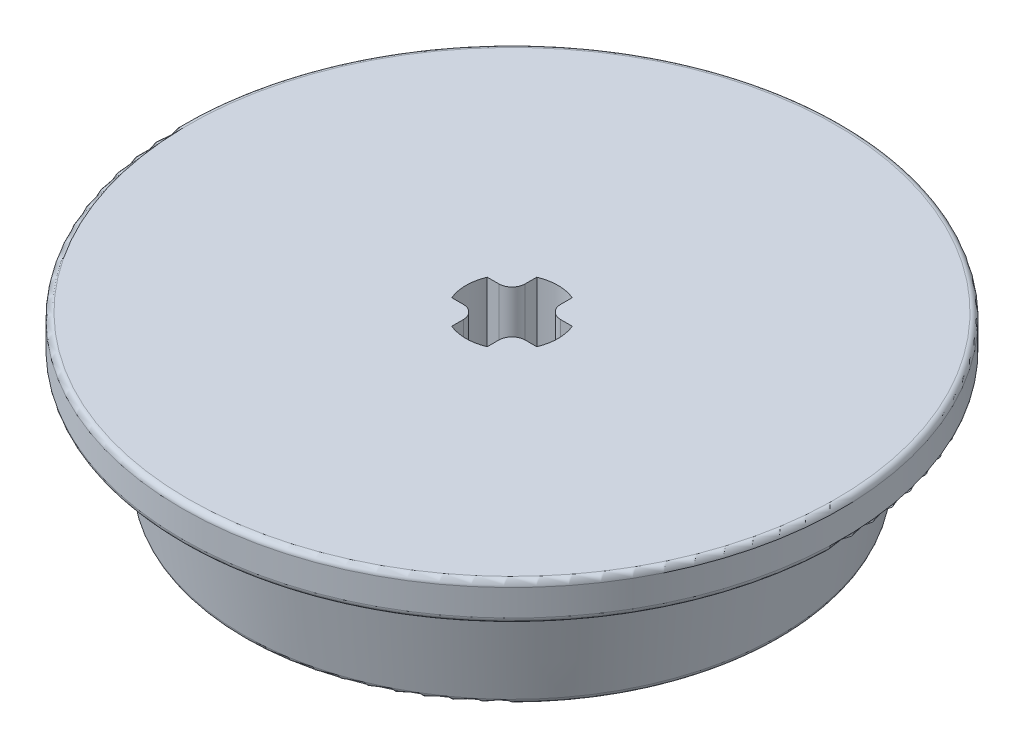
SolidWorks part; units mm, degrees
ref_plane "Front Plane" through (0, 0, 0) normal (0, 0, 1) x (1, 0, 0)
ref_plane "Top Plane" through (0, 0, 0) normal (0, 1, 0) x (1, 0, 0)
ref_plane "Right Plane" through (0, 0, 0) normal (1, 0, 0) x (0, 0, -1)
sketch "Sketch1" plane through (0, 0, 0) normal (0, 1, 0) x (1, 0, 0)
  line L2 (0, 0) -> (0, 47.5777) construction
  line L3 (0, 0) -> (50000, 0) construction
  line L6 (-0.89, 0.89) -> (0, 0) construction
  line L7 (0, 0) -> (0.89, 0.89) construction
  line L12 (2.39, 0) -> (2.39, 3.5727) construction
  line L13 (0, 2.39) -> (50000, 2.39) construction
  line L14 (-2.39, 0.4111) -> (-2.39, -49999.5889) construction
  line L15 (0.2318, -2.39) -> (-49999.7682, -2.39) construction
  line L16 (0, 0) -> (-0.89, -0.89) construction
  line L17 (0, 0) -> (0.89, -0.89) construction
  line L18 (-0.94, 0.94) -> (-2.2517, 0.94)
  line L19 (-2.2517, -0.94) -> (-0.94, -0.94)
  line L20 (-0.94, -0.94) -> (-0.94, -2.2517)
  line L21 (0.94, -2.2517) -> (0.94, -0.94)
  line L22 (0.94, -0.94) -> (2.2517, -0.94)
  line L23 (0.94, 0.94) -> (2.2517, 0.94)
  line L24 (0.94, 2.2517) -> (0.94, 0.94)
  line L25 (-0.94, 2.2517) -> (-0.94, 0.94)
  arc A4 (-2.2517, 0.94) -> (-2.2517, -0.94) centre (0, 0) ccw
  arc A5 (-0.94, -2.2517) -> (0.94, -2.2517) centre (0, 0) ccw
  arc A6 (2.2517, 0.94) -> (2.2517, -0.94) centre (0, 0) cw
  arc A7 (-0.94, 2.2517) -> (0.94, 2.2517) centre (0, 0) cw
  point P15 (0, 2.39)
  point P24 (2.39, 0)
  point P29 (-2.39, 0)
  point P30 (0, -2.39)
  line B0 (-0.89, 2.2181) -> (-0.89, 0.89) construction
  line B1 (-0.89, 0.89) -> (-2.2181, 0.89) construction
  line B2 (0.89, 2.2181) -> (0.89, 0.89) construction
  line B3 (0.89, 0.89) -> (2.2181, 0.89) construction
  line B4 (-2.2181, -0.89) -> (-0.89, -0.89) construction
  line B5 (-0.89, -0.89) -> (-0.89, -2.2181) construction
  line B6 (0.89, -2.2181) -> (0.89, -0.89) construction
  line B7 (0.89, -0.89) -> (2.2181, -0.89) construction
  arc B8 (-0.89, 2.2181) -> (0.89, 2.2181) centre (0, 0) cw construction
  arc B9 (-2.2181, 0.89) -> (-2.2181, -0.89) centre (0, 0) ccw construction
  arc B10 (2.2181, 0.89) -> (2.2181, -0.89) centre (0, 0) cw construction
  arc B11 (-0.89, -2.2181) -> (0.89, -2.2181) centre (0, 0) ccw construction
sketch_block_instance "Lego Axle - Unfilleted-1"
sketch_block "Lego Axle - Unfilleted" parameters "D1"=10.5762, "D2"=12.3972, "D3"=62.5785, "D4"=1.2287, "D5"=12.9019, "D6"=1.0841, "D7"=0.05
sketch "Sketch2" plane through (0, 0, 0) normal (0, 0, 1) x (1, 0, 0)
  line L0 (0, 0) -> (17.4605, 0)
  line L1 (200000.2318, 0) -> (-249999.7682, 0) construction
  line L2 (17.4605, 0) -> (17.4605, -2)
  line L3 (17.4605, -2) -> (15, -2)
  line L4 (15, -2) -> (14.1568, -8)
  line L5 (14.1568, -8) -> (0, -8)
  line L6 (0, -8) -> (0, 0)
  line L7 (0, 0) -> (0, 50000) construction
  dimension "D1" = 30
  dimension "D2" = 8
  dimension "D3" = 8
  dimension "D4" = 2
revolve "Revolve1" add sketch "Sketch2" angle 360 about L7
extrude "Cut-Extrude1" cut sketch "Sketch1" against normal through all
fillet "Fillet1" radius 0.7 4 edges at (-0.94, -4, 0.94) (0.94, -4, 0.94) (0.94, -4, -0.94) (-0.94, -4, -0.94)
fillet "Fillet2" radius 0.3 4 edges at (0, -8, -14.1568) (0, 0, -17.4605) (0, -2, -15) (0, -2, -17.4605)
